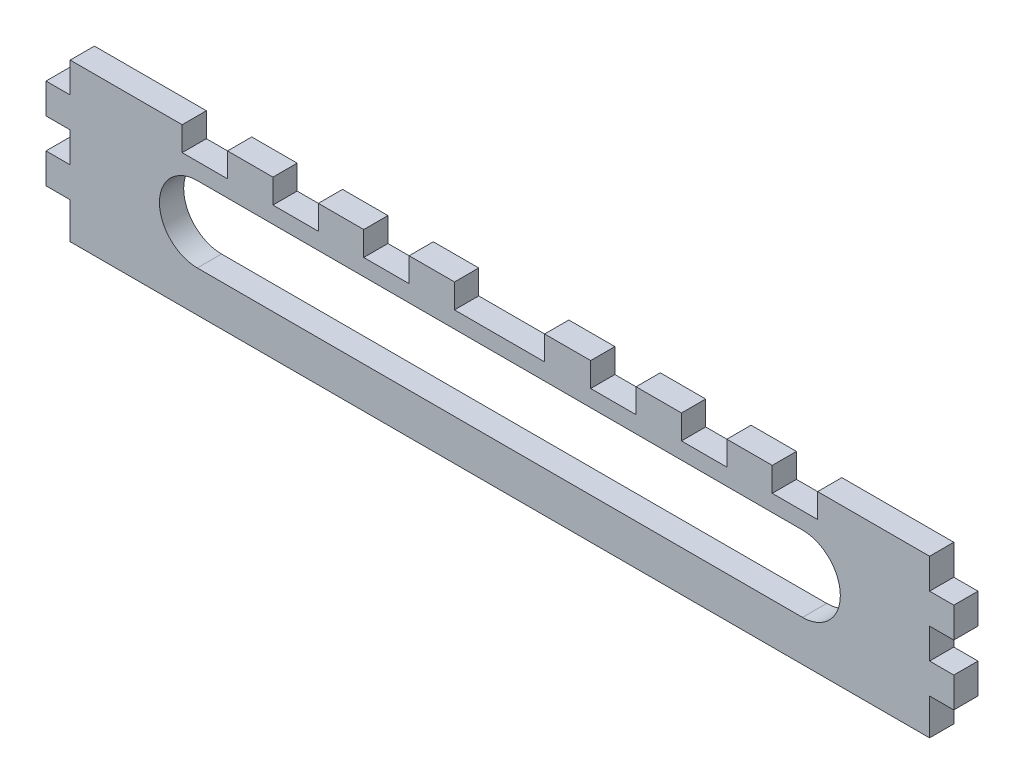
SolidWorks part; units mm, degrees
ref_plane "Plan de face" through (0, 0, 0) normal (0, 0, 1) x (1, 0, 0)
ref_plane "Plan de dessus" through (0, 0, 0) normal (0, 1, 0) x (1, 0, 0)
ref_plane "Plan de droite" through (0, 0, 0) normal (1, 0, 0) x (0, 0, -1)
sketch "Esquisse1" plane through (0, 0, 0) normal (0, 0, 1) x (1, 0, 0)
  line L1 (-150, -26) -> (150, -26)
  line L2 (-150, -26) -> (-150, 26)
  line L3 (-150, 26) -> (150, 26)
  line L4 (150, -26) -> (150, 26)
  line L5 (-150, -26) -> (150, 26) construction
  line L6 (-150, 26) -> (150, -26) construction
  point P0 (0, 0)
  dimension "D1" = 300
  dimension "D2" = 52
extrude "Boss.-Extru.1" add sketch "Esquisse1" along normal blind 8
sketch "Esquisse2" plane through (0, 0, 0) normal (0, 0, 1) x (1, 0, 0)
  line L0 (-150, 6) -> (-150, -4)
  line L1 (-150, 26) -> (-142, 26)
  line L2 (-150, 26) -> (-150, 16)
  line L3 (-150, 16) -> (-142, 16)
  line L4 (-142, 26) -> (-142, 16)
  line L5 (-150, 6) -> (-142, 6)
  line L6 (-142, 6) -> (-142, -4)
  line L7 (-150, -4) -> (-142, -4)
  line L8 (-150, -14) -> (-150, -24)
  line L9 (-150, -14) -> (-142, -14)
  line L10 (-142, -14) -> (-142, -24)
  line L11 (-150, -24) -> (-142, -24)
  dimension "D1" = 10
  dimension "D2" = 8
  dimension "D3" = 3
extrude "Enlèv. mat.-Extru.1" cut sketch "Esquisse2" along normal through all
sketch "Esquisse3" plane through (0, 0, 0) normal (0, 0, 1) x (1, 0, 0)
  line L1 (-150, -26) -> (-142, -26)
  line L2 (-150, -26) -> (-150, -24)
  line L3 (-150, -24) -> (-142, -24)
  line L4 (-142, -26) -> (-142, -24)
extrude "Enlèv. mat.-Extru.2" cut sketch "Esquisse3" along normal through all
mirror "Symétrie1" about plane through (0, 0, 0) normal (1, 0, 0) of "Enlèv. mat.-Extru.2", "Enlèv. mat.-Extru.1"
sketch "Esquisse4" plane through (0, 0, 0) normal (0, 0, 1) x (1, 0, 0)
  line L0 (-100, 0) -> (100, 0) construction
  line L1 (-100, 12.5) -> (100, 12.5)
  line L2 (-100, -12.5) -> (100, -12.5)
  arc A0 (-100, 12.5) -> (-100, -12.5) centre (-100, 0) ccw
  arc A1 (100, -12.5) -> (100, 12.5) centre (100, 0) ccw
  point P2 (0, 0)
  dimension "D2" = 100
  dimension "D1" = 25
extrude "Enlèv. mat.-Extru.3" cut sketch "Esquisse4" along normal through all
sketch "Esquisse5" plane through (0, 0, 0) normal (0, 0, 1) x (1, 0, 0)
  line L0 (0, 0) -> (0, 18) construction
  line L1 (142, 26) -> (-142, 26) construction
  line L2 (0, 26) -> (-15, 26)
  line L4 (0, 18) -> (-15, 18)
  line L5 (-15, 26) -> (-15, 18)
  line L6 (-30, 26) -> (-30, 18)
  line L7 (-30, 26) -> (-45, 26)
  line L8 (-45, 26) -> (-45, 18)
  line L9 (-30, 18) -> (-45, 18)
  line L10 (-60, 26) -> (-60, 18)
  line L11 (-60, 26) -> (-75, 26)
  line L12 (-75, 26) -> (-75, 18)
  line L13 (-60, 18) -> (-75, 18)
  line L14 (-90, 26) -> (-90, 18)
  line L15 (-90, 26) -> (-105, 26)
  line L16 (-105, 26) -> (-105, 18)
  line L17 (-90, 18) -> (-105, 18)
  line L18 (30, 26) -> (45, 26)
  line L19 (45, 26) -> (45, 18)
  line L20 (30, 18) -> (45, 18)
  line L21 (30, 26) -> (30, 18)
  line L22 (60, 26) -> (75, 26)
  line L23 (75, 26) -> (75, 18)
  line L24 (60, 18) -> (75, 18)
  line L25 (60, 26) -> (60, 18)
  line L26 (90, 26) -> (105, 26)
  line L27 (105, 26) -> (105, 18)
  line L28 (90, 18) -> (105, 18)
  line L29 (90, 26) -> (90, 18)
  line L31 (0, 26) -> (14.7774, 26)
  line L33 (0, 18) -> (14.7774, 18)
  line L34 (14.7774, 26) -> (14.7774, 18)
  dimension "D1" = 15
  dimension "D2" = 8
  dimension "D3" = 4
extrude "Enlèv. mat.-Extru.4" cut sketch "Esquisse5" along normal blind 10 contours L14 L17 L16 L15 | L10 L13 L12 L11 | L6 L9 L8 L7 | L2 L5 L4 L33 L34 L31 | L18 L19 L20 L21 | L22 L23 L24 L25 | L26 L27 L28 L29
